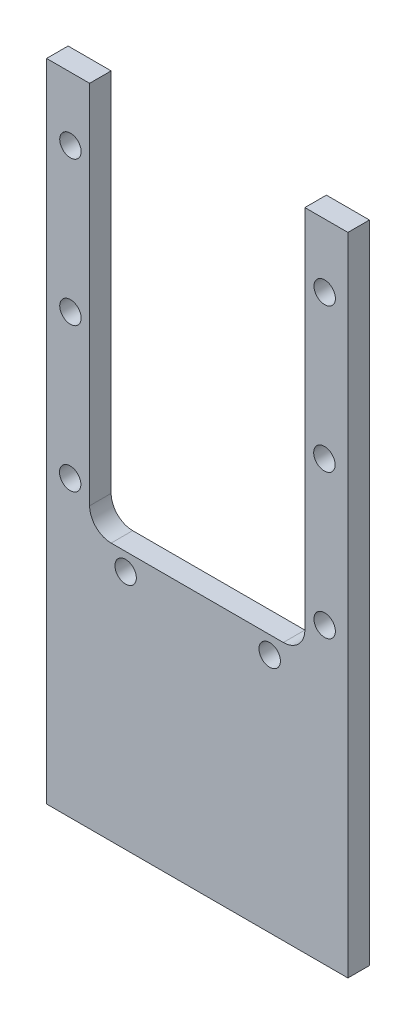
SolidWorks part; units mm, degrees
material "6061-T6 (SS)"
ref_plane "Front Plane" through (0, 0, 0) normal (0, 0, 1) x (1, 0, 0)
ref_plane "Top Plane" through (0, 0, 0) normal (0, 1, 0) x (1, 0, 0)
ref_plane "Right Plane" through (0, 0, 0) normal (1, 0, 0) x (0, 0, -1)
sketch "Sketch1" plane through (0, 0, 0) normal (0, 0, 1) x (1, 0, 0)
  line L0 (0, 0) -> (0, 76.2)
  line L1 (0, 76.2) -> (5.08, 76.2)
  line L2 (5.08, 76.2) -> (5.08, 30.48)
  line L3 (5.08, 30.48) -> (30.48, 30.48)
  line L4 (30.48, 30.48) -> (30.48, 76.2)
  line L5 (30.48, 76.2) -> (35.56, 76.2)
  line L6 (35.56, 76.2) -> (35.56, 0)
  line L7 (35.56, 0) -> (0, 0)
  dimension "D1" = 76.2
  dimension "D2" = 5.08
  dimension "D3" = 45.72
  dimension "D4" = 25.4
  dimension "D5" = 45.72
  dimension "D6" = 5.08
  dimension "D7" = 76.2
extrude "Boss-Extrude1" add sketch "Sketch1" along normal blind 2.54
fillet "Fillet1" radius 2.54 2 edges at (30.48, 30.48, 1.27) (5.08, 30.48, 1.27)
hole_wizard "#39 (0.0995) Diameter Hole1" positions "Sketch6" profile "Sketch5" hole size "#39" standard "ANSI Inch" end condition through all
sketch "Sketch6" plane through (0, 0, 2.54) normal (0, 0, 1) x (1, 0, 0)
  line L2 (35.56, 0) -> (35.56, 76.2) construction
  line L3 (0, 0) -> (35.56, 0) construction
  point P0 (32.8208, 68.7099)
  point P2 (32.7849, 51.6859)
  point P5 (32.816, 34.6937)
  point P7 (26.3292, 28.4037)
  point P9 (9.3292, 28.4037)
  point P11 (2.7849, 34.6859)
  point P14 (2.816, 51.6969)
  point P16 (2.816, 68.7099)
  dimension "D1" = 32.7751
  dimension "D2" = 2.7392
  dimension "D3" = 0.0048
  dimension "D4" = 0.0311
  dimension "D5" = 6.4557
  dimension "D6" = 17
  dimension "D7" = 6.5132
  dimension "D8" = 28.4037
  dimension "D9" = 34.6859
  dimension "D10" = 34.6937
  dimension "D11" = 51.6859
  dimension "D12" = 51.6969
  dimension "D13" = 68.7099
sketch "Sketch5" plane through (32.8208, 68.7099, 2.54) normal (1, 0, 0) x (0, -1, 0)
  line L0 (0, 0) -> (0, 2.54)
  line L1 (0, 2.54) -> (1.2636, 2.54)
  line L2 (1.2636, 2.54) -> (1.2636, 0)
  line L5 (1.2636, 0) -> (0, 0)
  line L11 (0, -6.35) -> (0, 107.95) construction
  dimension "Thru Hole Dia." = 2.5273
  dimension "Thru Hole Depth" = 2.54
